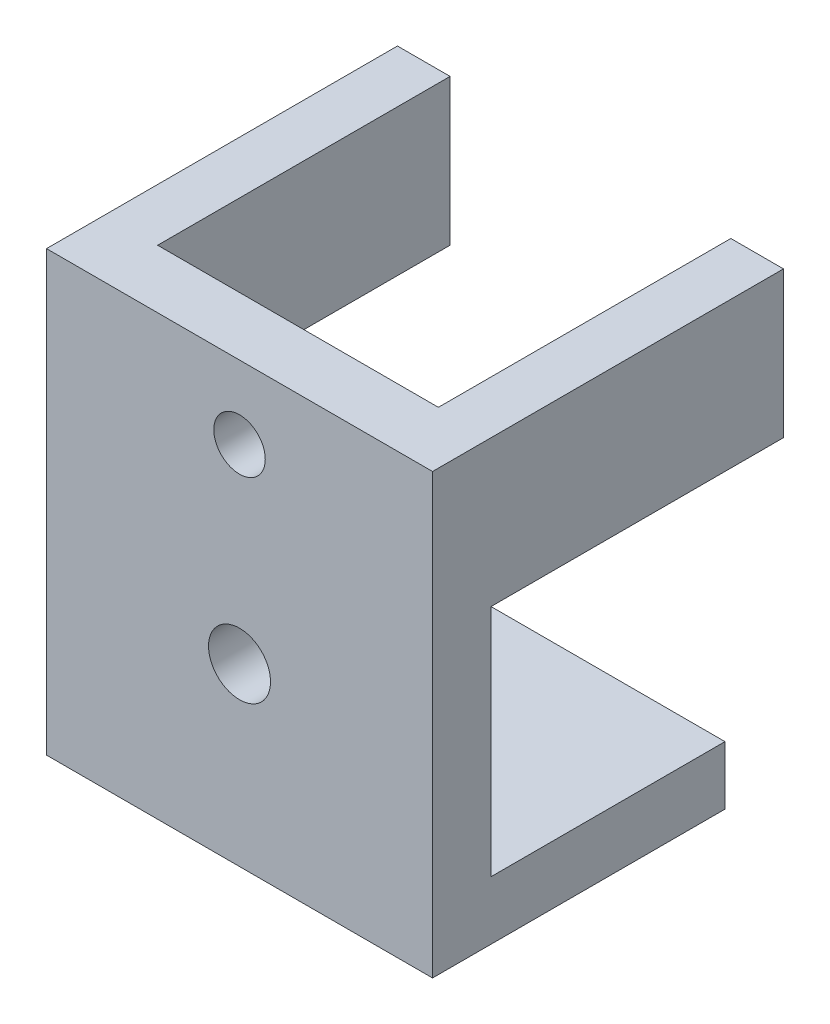
SolidWorks part; units mm, degrees
ref_plane "Front Plane" through (0, 0, 0) normal (0, 0, 1) x (1, 0, 0)
ref_plane "Top Plane" through (0, 0, 0) normal (0, 1, 0) x (1, 0, 0)
ref_plane "Right Plane" through (0, 0, 0) normal (1, 0, 0) x (0, 0, -1)
sketch "Sketch2" plane through (0, 0, 0) normal (0, 0, 1) x (1, 0, 0)
  line L1 (0, 0) -> (33, 0)
  line L2 (0, 0) -> (0, 37.5)
  line L3 (0, 37.5) -> (33, 37.5)
  line L4 (33, 0) -> (33, 37.5)
  dimension "D1" = 37.5
  dimension "D2" = 33
extrude "Boss-Extrude1" add sketch "Sketch2" along normal blind 5
sketch "Sketch3" plane through (0, 0, 0) normal (0, 0, 1) x (1, 0, 0)
  line L0 (33, 0) -> (33, 37.5) construction
  line L1 (0, 0) -> (33, 0)
  line L2 (0, 0) -> (0, 5)
  line L3 (0, 5) -> (33, 5)
  line L4 (33, 0) -> (33, 5)
  dimension "D1" = 5
extrude "Boss-Extrude2" add sketch "Sketch3" against normal blind 20
sketch "Sketch6" plane through (0, 0, 0) normal (0, -1, 0) x (1, 0, 0)
  line L0 (0, -20) -> (33, -20) construction
  line L2 (16.5, 5) -> (16.5, -20) construction
  line L3 (0, 5) -> (33, 5) construction
  line L4 (0, -20) -> (33, -20) construction
  circle A0 centre (16.5, -10) radius 2.65
  dimension "D1" = 5.3
  dimension "D2" = 10
extrude "Cut-Extrude2" cut sketch "Sketch6" against normal blind 10
sketch "Sketch7" plane through (0, 0, 0) normal (0, 0, -1) x (-1, 0, 0)
  line L0 (0, 0) -> (-33, 0) construction
  line L2 (-16.5, 37.5) -> (-16.5, 0) construction
  line L3 (-33, 37.5) -> (0, 37.5) construction
  line L4 (0, 0) -> (-33, 0) construction
  circle A0 centre (-16.5, 15) radius 2.65
  dimension "D1" = 5.3
  dimension "D2" = 15
extrude "Cut-Extrude3" cut sketch "Sketch7" against normal blind 10
sketch "Sketch8" plane through (0, 0, 0) normal (0, 0, -1) x (-1, 0, 0)
  line L1 (-33, 37.5) -> (-28.5, 37.5)
  line L2 (-33, 37.5) -> (-33, 25)
  line L3 (-33, 25) -> (-28.5, 25)
  line L4 (-28.5, 37.5) -> (-28.5, 25)
  line L5 (0, 37.5) -> (-4.5, 37.5)
  line L6 (0, 37.5) -> (0, 25)
  line L7 (0, 25) -> (-4.5, 25)
  line L8 (-4.5, 37.5) -> (-4.5, 25)
  dimension "D1" = 4.5
  dimension "D2" = 4.5
  dimension "D3" = 12.5
  dimension "D4" = 12.5
extrude "Boss-Extrude3" add sketch "Sketch8" along normal blind 25
sketch "Sketch9" plane through (0, 0, 5) normal (0, 0, 1) x (1, 0, 0)
  line L0 (33, 37.5) -> (0, 37.5) construction
  line L2 (16.5, 37.5) -> (16.5, 0) construction
  line L3 (0, 0) -> (33, 0) construction
  circle A0 centre (16.5, 31.25) radius 2.2
  dimension "D1" = 4.4
  dimension "D2" = 6.25
extrude "Cut-Extrude4" cut sketch "Sketch9" against normal blind 10
